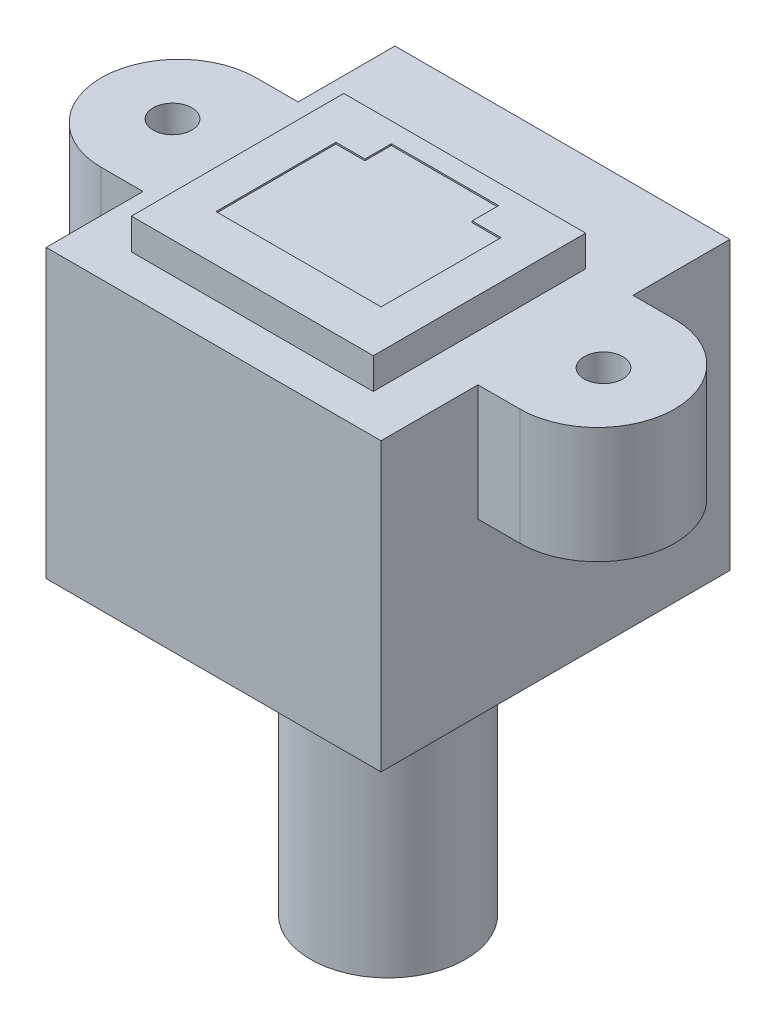
SolidWorks part; units mm, degrees
ref_plane "前视基准面" through (0, 0, 0) normal (0, 0, 1) x (1, 0, 0)
ref_plane "上视基准面" through (0, 0, 0) normal (0, 1, 0) x (1, 0, 0)
ref_plane "右视基准面" through (0, 0, 0) normal (1, 0, 0) x (0, 0, -1)
sketch "草图1" plane through (0, 0, 0) normal (0, 1, 0) x (1, 0, 0)
  line L1 (7.8, -6.85) -> (-7.8, -6.85)
  line L2 (7.8, -6.85) -> (7.8, 6.85)
  line L3 (7.8, 6.85) -> (-7.8, 6.85)
  line L4 (-7.8, -6.85) -> (-7.8, 6.85)
  line L5 (7.8, -6.85) -> (-7.8, 6.85) construction
  line L6 (7.8, 6.85) -> (-7.8, -6.85) construction
  point P0 (0, 0)
  dimension "D1" = 15.6
  dimension "D2" = 13.7
extrude "凸台-拉伸1" add sketch "草图1" along normal blind 2
sketch "草图3" plane through (0, 0, 0) normal (0, -1, 0) x (1, 0, 0)
  line L0 (0, 0) -> (0, 4.4279) construction
  line L1 (-10.8, 9.35) -> (10.8, 9.35)
  line L2 (-10.8, 9.35) -> (-10.8, 3.1)
  line L3 (-10.8, -13.15) -> (10.8, -13.15)
  line L4 (10.8, 9.35) -> (10.8, 3.1)
  line L5 (-7.8, 6.85) -> (7.8, 6.85) construction
  line L6 (-13.5, 3.1) -> (-10.8, 3.1)
  line L7 (-13.5, -6.9) -> (-10.8, -6.9)
  line L8 (13.5, 3.1) -> (10.8, 3.1)
  line L9 (-10.8, -6.9) -> (-10.8, -13.15)
  line L10 (10.8, -6.9) -> (13.5, -6.9)
  line L11 (10.8, -6.9) -> (10.8, -13.15)
  line L12 (-10.8, 9.35) -> (-10.8, -13.15) construction
  arc A0 (13.5, -6.9) -> (13.5, 3.1) centre (13.5, -1.9) ccw
  arc A1 (-13.5, 3.1) -> (-13.5, -6.9) centre (-13.5, -1.9) ccw
  point P10 (-10.8, -1.9)
  dimension "D4" = 27
  dimension "D5" = 10
  dimension "D1" = 21.6
  dimension "D2" = 22.5
  dimension "D3" = 2.5
extrude "凸台-拉伸2" add sketch "草图3" along normal blind 7.5
sketch "草图4" plane through (0, -7.5, 0) normal (0, -1, 0) x (1, 0, 0)
  line L1 (-10.8, 9.35) -> (10.8, 9.35)
  line L2 (-10.8, 9.35) -> (-10.8, -13.15)
  line L3 (-10.8, -13.15) -> (10.8, -13.15)
  line L4 (10.8, 9.35) -> (10.8, -13.15)
extrude "凸台-拉伸3" add sketch "草图4" along normal blind 15
chamfer "倒角1" distance 4 angle 45 4 edges at (0, -22.5, 9.35) (10.8, -22.5, -1.9) (0, -22.5, -13.15) (-10.8, -22.5, -1.9)
sketch "草图5" plane through (0, -22.5, 0) normal (0, -1, 0) x (1, 0, 0)
  line L0 (0, 5.35) -> (0, -9.15) construction
  line L1 (6.8, 5.35) -> (-6.8, 5.35) construction
  line L2 (-6.8, -9.15) -> (6.8, -9.15) construction
  line L3 (6.8, -1.9) -> (-6.8, -1.9) construction
  line L4 (6.8, -9.15) -> (6.8, 5.35) construction
  line L5 (-6.8, 5.35) -> (-6.8, -9.15) construction
  circle A0 centre (0, -1.9) radius 5
  dimension "D1" = 10
extrude "凸台-拉伸4" add sketch "草图5" along normal blind 15
sketch "草图6" plane through (0, 2, 0) normal (0, 1, 0) x (1, 0, 0)
  line L0 (0, 0) -> (0, 6.85) construction
  line L1 (5.3267, -3.8696) -> (-5.3267, -3.8696)
  line L2 (5.3267, -3.8696) -> (5.3267, 3.8696)
  line L3 (5.3267, 3.8696) -> (3.4587, 3.8696)
  line L4 (-5.3267, -3.8696) -> (-5.3267, 3.8696)
  line L5 (5.3267, -3.8696) -> (-5.3267, 3.8696) construction
  line L6 (5.3267, 3.8696) -> (-5.3267, -3.8696) construction
  line L8 (-3.4587, 3.8696) -> (-3.4587, 5.5752)
  line L9 (-3.4587, 5.5752) -> (3.4587, 5.5752)
  line L10 (3.4587, 3.8696) -> (3.4587, 5.5752)
  line L11 (7.8, 6.85) -> (-7.8, 6.85) construction
  line L12 (-3.4587, 3.8696) -> (-5.3267, 3.8696)
  point P0 (0, 0)
extrude "切除-拉伸1" cut sketch "草图6" against normal blind 0.1
hole_wizard "M3 螺纹孔1" positions "草图7" profile "草图8" tap size "M3" standard "GB" end condition up to next
sketch "草图7" plane through (0, 0, 0) normal (0, 1, 0) x (1, 0, 0)
  line L0 (0, 0) -> (0, 4.8642) construction
  arc A0 (-13.5, 6.9) -> (-13.5, -3.1) centre (-13.5, 1.9) ccw construction
  point P0 (13.9, 1.9)
  point P2 (-13.9, 1.9)
  point P19 (-18.5, 1.9)
  dimension "D1" = 27.8
sketch "草图8" plane through (13.9, 0, -1.9) normal (1, 0, 0) x (0, 0, 1)
  line L0 (0, 0) -> (0, 7.5)
  line L1 (0, 7.5) -> (1.25, 7.5)
  line L2 (1.25, 7.5) -> (1.25, 0)
  line L5 (1.25, 0) -> (0, 0)
  line L11 (0, -6.35) -> (0, 107.95) construction
  dimension "通孔螺纹孔钻头直径" = 2.5
  dimension "通孔螺纹孔钻头深度" = 7.5
cosmetic thread "孔螺蚊线1" parameters "D2"=3
cosmetic thread "孔螺蚊线2" parameters "D2"=3
